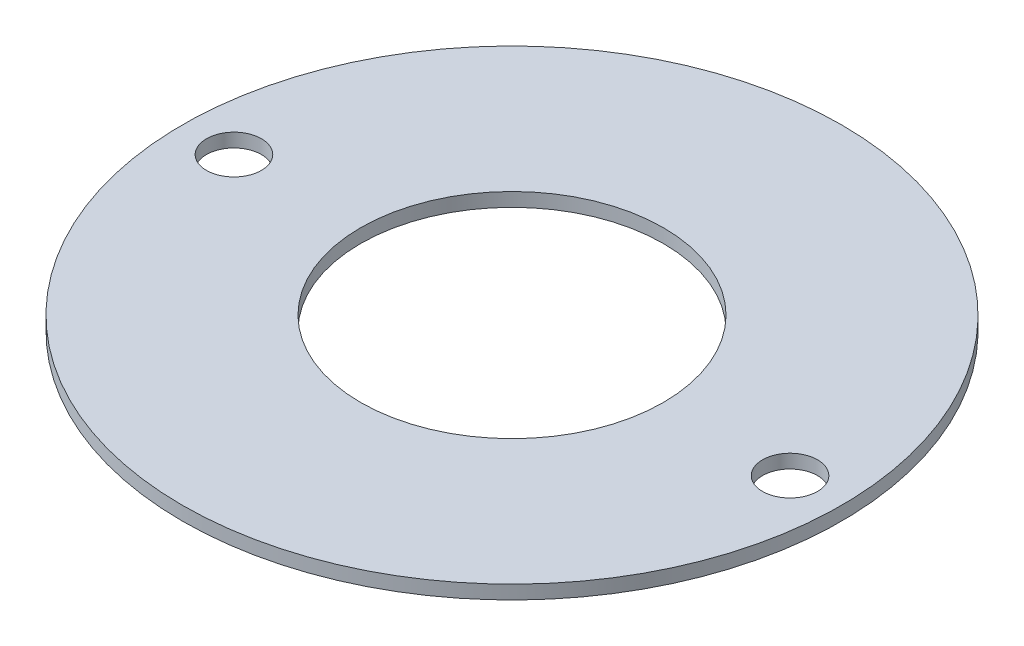
SolidWorks part; units mm, degrees
ref_plane "Front Plane" through (0, 0, 0) normal (0, 0, 1) x (1, 0, 0)
ref_plane "Top Plane" through (0, 0, 0) normal (0, 1, 0) x (1, 0, 0)
ref_plane "Right Plane" through (0, 0, 0) normal (1, 0, 0) x (0, 0, -1)
sketch "Sketch1" plane through (0, 0, 0) normal (0, 1, 0) x (1, 0, 0)
  circle A0 centre (0, 0) radius 76.2
  dimension "D1" = 152.4
extrude "Boss-Extrude1" add sketch "Sketch1" along normal blind 3.175
sketch "Sketch2" plane through (0, 3.175, 0) normal (0, 1, 0) x (1, 0, 0)
  circle A0 centre (0, 0) radius 35
  dimension "D1" = 70
extrude "Cut-Extrude1" cut sketch "Sketch2" against normal blind 3.175
sketch "Sketch3" plane through (0, 3.175, 0) normal (0, 1, 0) x (1, 0, 0)
  line L0 (-76.2, 0) -> (76.2, 0) construction
  line L1 (-51.5875, 51.5875) -> (51.5875, 51.5875) construction
  line L2 (-51.5875, 51.5875) -> (-51.5875, -51.5875) construction
  line L3 (-51.5875, -51.5875) -> (51.5875, -51.5875) construction
  line L4 (51.5875, 51.5875) -> (51.5875, -51.5875) construction
  circle A0 centre (0, 0) radius 76.2 construction
  circle A1 centre (-64.2875, 0) radius 6.35
  circle A2 centre (64.2875, 0) radius 6.35
  dimension "D1" = 12.7
  dimension "D2" = 12.7
  dimension "D3" = 12.7
  dimension "D4" = 12.7
extrude "Cut-Extrude2" cut sketch "Sketch3" against normal blind 10
sketch "Sketch4" plane through (0, 3.175, 0) normal (0, 1, 0) x (1, 0, 0)
  line L1 (50, -50) -> (-50, -50) construction
  line L2 (50, -50) -> (50, 50) construction
  line L3 (50, 50) -> (-50, 50) construction
  line L4 (-50, -50) -> (-50, 50) construction
  line L5 (50, -50) -> (-50, 50) construction
  line L6 (50, 50) -> (-50, -50) construction
  point P0 (0, 0)
  dimension "D1" = 100
  dimension "D2" = 100
sketch "Sketch5" plane through (0, 3.175, 0) normal (0, 1, 0) x (1, 0, 0)
  line L0 (-50, 24.6) -> (-59.525, 24.6) construction
  line L1 (-50, -50) -> (-50, 50) construction
  line L2 (-50, -24.6) -> (-59.525, -24.6) construction
  line L3 (50, 50) -> (-50, 50) construction
  line L4 (50, -50) -> (-50, -50) construction
  line L5 (-50, 50) -> (50, -50) construction
  line L6 (-50, -50) -> (50, 50) construction
  line L7 (24.6, 50) -> (24.6, 59.525) construction
  line L8 (-50, 50) -> (50, 50) construction
  line L9 (-50, 50) -> (-50, -50) construction
  line L10 (-50, -50) -> (50, -50) construction
  line L11 (50, 50) -> (50, -50) construction
  line L12 (-24.6, 50) -> (-24.6, 59.525) construction
  line L13 (50, 24.6) -> (59.525, 24.6) construction
  line L14 (-24.6, -50) -> (-24.6, -59.525) construction
  line L15 (24.6, -50) -> (24.6, -59.525) construction
  line L16 (50, -24.6) -> (59.525, -24.6) construction
  dimension "D1" = 25.4
  dimension "D2" = 25.4
  dimension "D3" = 9.525
  dimension "D4" = 9.525
